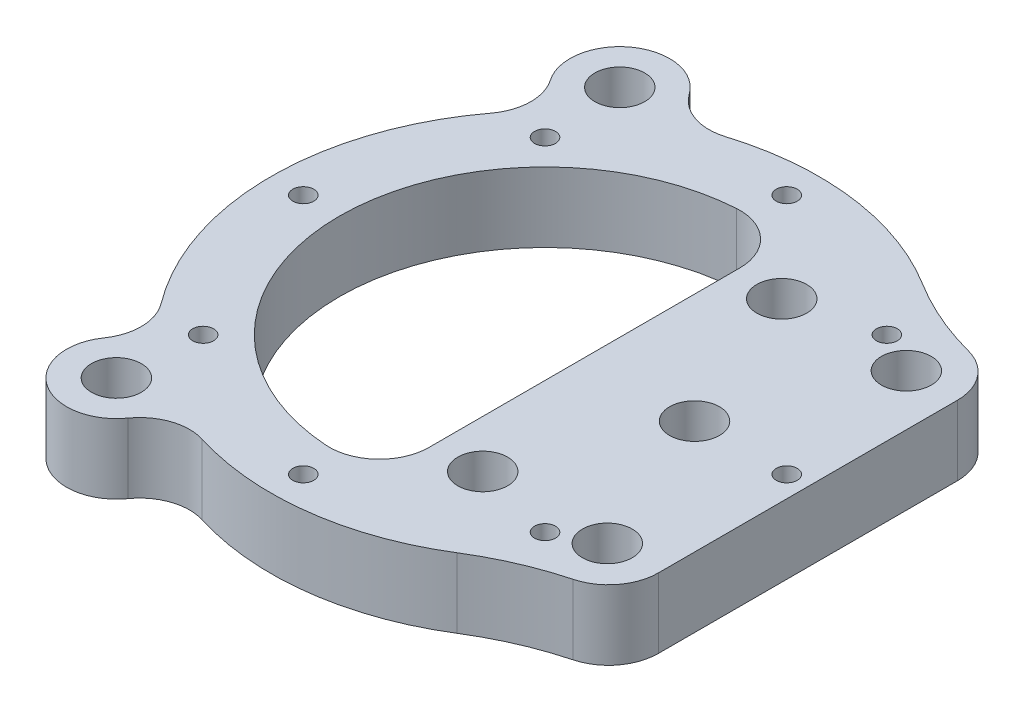
SolidWorks part; units mm, degrees
material "7075-T6 (SN)"
ref_plane "Front" through (0, 0, 0) normal (0, 0, 1) x (1, 0, 0)
ref_plane "Top" through (0, 0, 0) normal (0, 1, 0) x (1, 0, 0)
ref_plane "Right" through (0, 0, 0) normal (1, 0, 0) x (0, 0, -1)
sketch "Sketch1" plane through (0, 0, 0) normal (0, 1, 0) x (1, 0, 0)
  line L16 (-68.8748, 36.9371) -> (-53.8748, 36.9371)
  line L24 (-68.8748, -43.0629) -> (-53.8748, -43.0629)
  line L25 (-53.8748, 36.9371) -> (-53.8748, -43.0629)
  line L29 (-133.9431, 53.188) -> (-129.546, 46.9329)
  line L30 (-150.3049, 41.6862) -> (-145.9077, 35.4311)
  line L32 (-150.3049, -47.812) -> (-145.9077, -41.5569)
  line L33 (-133.9431, -59.3138) -> (-129.546, -53.0587)
  arc A24 (-145.9077, 35.4311) -> (-145.9077, -41.5569) centre (-106.624, -3.0629) ccw
  arc A25 (-133.9431, 53.188) -> (-150.3049, 41.6862) centre (-142.124, 47.4371) ccw
  arc A27 (-150.3049, -47.812) -> (-133.9431, -59.3138) centre (-142.124, -53.5629) ccw
  arc A30 (-129.546, -53.0587) -> (-68.8748, -43.0629) centre (-106.624, -3.0629) ccw
  arc A32 (-68.8748, 36.9371) -> (-129.546, 46.9329) centre (-106.624, -3.0629) ccw
  point P0 (-76.624, -3.0629)
  dimension "D1" = 110
  dimension "D2" = 30
  dimension "D3" = 10
  dimension "D4" = 10
  dimension "D5" = 80
  dimension "D6" = 15
extrude "Boss-Extrude1" add sketch "Sketch1" along normal blind 14
fillet "Fillet1" radius 10 6 edges at (-53.8748, 7, 43.0629) (-129.546, 7, 53.0587) (-145.9077, 7, 41.5569) (-129.546, 7, -46.9329) (-53.8748, 7, -36.9371) (-145.9077, 7, -35.4311)
fillet "Fillet2" radius 60 2 edges at (-68.8748, 7, 43.0629) (-68.8748, 7, -36.9371)
sketch "Sketch2" plane through (0, 14, 0) normal (0, 1, 0) x (1, 0, 0)
  circle A0 centre (-106.624, -3.0629) radius 48.5 construction
  circle A1 centre (-106.624, 45.4371) radius 2.1
  circle A2 centre (-72.3293, 31.2318) radius 2.1
  circle A3 centre (-58.124, -3.0629) radius 2.1
  circle A4 centre (-72.3293, -37.3576) radius 2.1
  circle A5 centre (-106.624, -51.5629) radius 2.1
  circle A6 centre (-140.9187, -37.3576) radius 2.1
  circle A7 centre (-155.124, -3.0629) radius 2.1
  circle A8 centre (-140.9187, 31.2318) radius 2.1
  circle A9 centre (-106.624, -3.0629) radius 3.0629
  point P21 (-106.624, -3.0629)
  dimension "D1" = 97
  dimension "D3" = 4.2
  dimension "D2" = 8
extrude "Cut-Extrude1" cut sketch "Sketch2" against normal through all
sketch "Sketch3" plane through (0, 14, 0) normal (0, 1, 0) x (1, 0, 0)
  circle A0 centre (-142.124, 47.4371) radius 2.5
  circle A1 centre (-142.124, -53.5629) radius 2.5
  dimension "D1" = 5
extrude "Cut-Extrude2" cut sketch "Sketch3" against normal blind 10
hole_wizard "CBORE for M5 Hex Socket Head Cap Screw1" positions "Sketch4" profile "Sketch6" counterbore size "M5" standard "DIN"
sketch "Sketch4" plane through (0, 14, 0) normal (0, 1, 0) x (1, 0, 0)
  point P0 (-89.124, 26.9371)
  point P2 (-64.124, 26.9371)
  point P4 (-76.624, -3.0629)
  point P6 (-89.124, -33.0629)
  point P8 (-64.124, -33.0629)
sketch "Sketch6" plane through (-89.124, 14, -26.9371) normal (1, 0, 0) x (0, 0, 1)
  line L0 (0, 0) -> (0, 26.6524)
  line L1 (0, 26.6524) -> (2.75, 25)
  line L2 (2.75, 25) -> (2.75, 8)
  line L3 (2.75, 8) -> (5, 8)
  line L4 (5, 8) -> (5, 0)
  line L5 (5, 0) -> (0, 0)
  line L10 (0, 26.6524) -> (-2.75, 25) construction
  line L11 (0, -6.35) -> (0, 107.95) construction
  dimension "Hole Dia." = 5.5
  dimension "Hole Depth" = 25
  dimension "C'Bore Dia." = 10
  dimension "C'Bore Depth" = 8
  dimension "Drill Angle" = 118
sketch "Sketch7" plane through (0, 14, 0) normal (0, 1, 0) x (1, 0, 0)
  line L4 (-98.6924, -43.5432) -> (-98.6924, 37.4174)
  line L5 (-113.7858, -43.6864) -> (-99.4621, 37.5606) construction
  line L6 (-113.7858, 37.5606) -> (-99.4621, -43.6864) construction
  arc A0 (-98.6924, 37.4174) -> (-98.6924, -43.5432) centre (-106.624, -3.0629) ccw
  dimension "D1" = 82.5
extrude "Cut-Extrude3" cut sketch "Sketch7" against normal blind 25
fillet "Fillet3" radius 10 2 edges at (-98.6924, 7, 43.5432) (-98.6924, 7, -37.4174)
hole_wizard "CBORE for M5 Hex Socket Head Cap Screw2" positions "Sketch8" profile "Sketch9" counterbore size "M5" standard "DIN"
sketch "Sketch8" plane through (0, 14, 0) normal (0, 1, 0) x (1, 0, 0)
  point P0 (-142.124, 47.4371)
  point P3 (-142.124, -53.5629)
sketch "Sketch9" plane through (-142.124, 14, -47.4371) normal (1, 0, 0) x (0, 0, 1)
  line L0 (0, 0) -> (0, 26.6524)
  line L1 (0, 26.6524) -> (2.75, 25)
  line L2 (2.75, 25) -> (2.75, 8)
  line L3 (2.75, 8) -> (5, 8)
  line L4 (5, 8) -> (5, 0)
  line L5 (5, 0) -> (0, 0)
  line L10 (0, 26.6524) -> (-2.75, 25) construction
  line L11 (0, -6.35) -> (0, 107.95) construction
  dimension "Hole Dia." = 5.5
  dimension "Hole Depth" = 25
  dimension "C'Bore Dia." = 10
  dimension "C'Bore Depth" = 8
  dimension "Drill Angle" = 118
